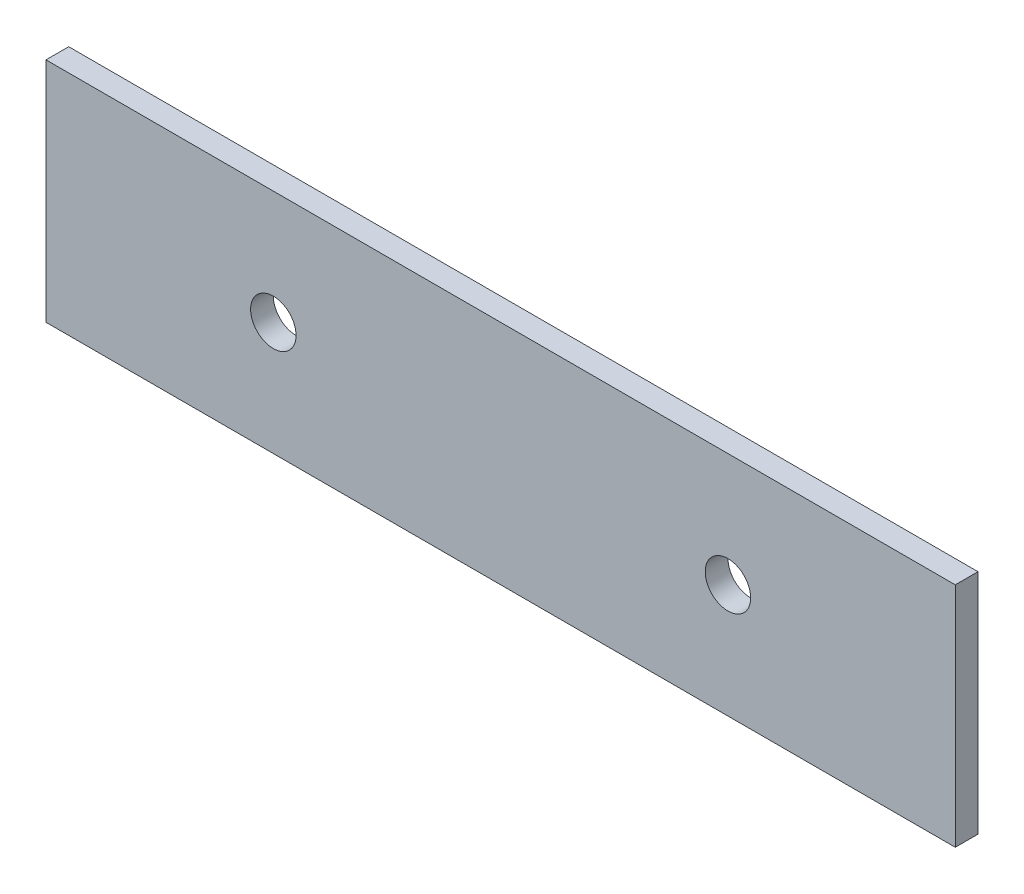
SolidWorks part; units mm, degrees
ref_plane "Front Plane" through (0, 0, 0) normal (0, 0, 1) x (1, 0, 0)
ref_plane "Top Plane" through (0, 0, 0) normal (0, 1, 0) x (1, 0, 0)
ref_plane "Right Plane" through (0, 0, 0) normal (1, 0, 0) x (0, 0, -1)
sketch "Sketch1" plane through (0, 0, 0) normal (0, 0, 1) x (1, 0, 0)
  line L1 (-40, 10) -> (40, 10)
  line L2 (-40, 10) -> (-40, -10)
  line L3 (-40, -10) -> (40, -10)
  line L4 (40, 10) -> (40, -10)
  line L5 (-40, 10) -> (40, -10) construction
  line L6 (-40, -10) -> (40, 10) construction
  point P0 (0, 0)
  dimension "D1" = 20
  dimension "D2" = 80
extrude "Boss-Extrude1" add sketch "Sketch1" along normal blind 2
sketch "Sketch2" plane through (0, 0, 2) normal (0, 0, 1) x (1, 0, 0)
  line L0 (-40, 10) -> (-40, -10) construction
  line L1 (40, -10) -> (40, 10) construction
  line L2 (-40, -10) -> (40, -10) construction
  circle A0 centre (-20, 0) radius 2
  circle A1 centre (20, 0) radius 2
  dimension "D1" = 4
  dimension "D2" = 4
  dimension "D3" = 20
  dimension "D4" = 20
  dimension "D5" = 10
  dimension "D6" = 10
extrude "Cut-Extrude1" cut sketch "Sketch2" against normal through all
